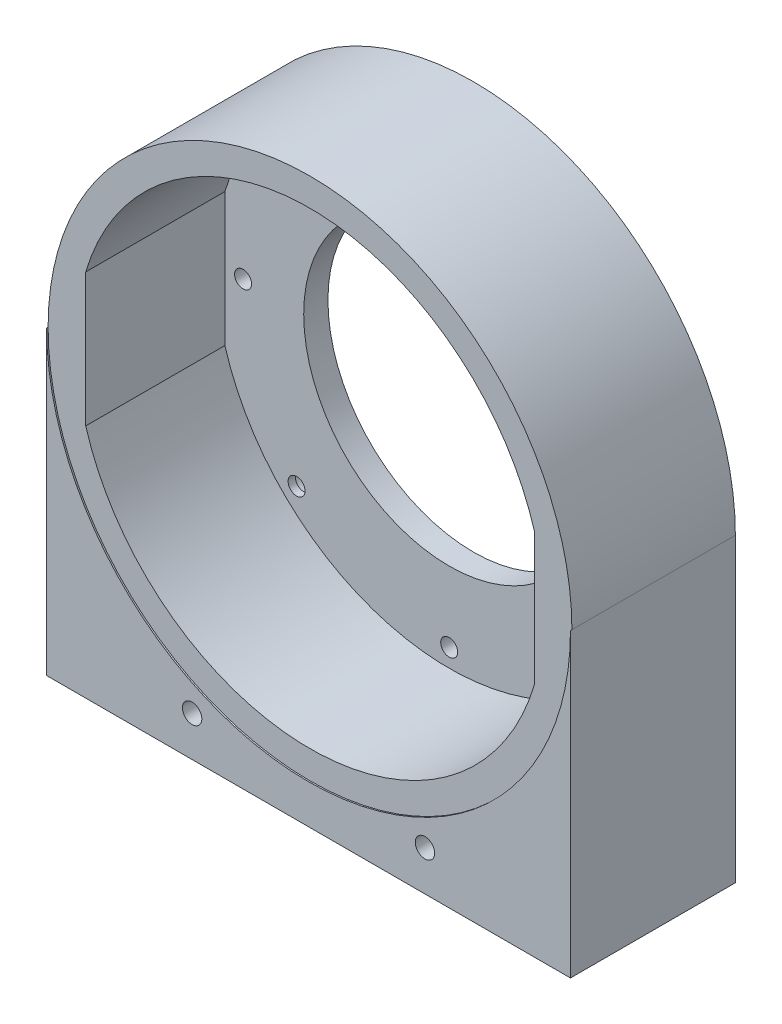
SolidWorks part; units mm, degrees
ref_plane "Front Plane" through (0, 0, 0) normal (0, 0, 1) x (1, 0, 0)
ref_plane "Top Plane" through (0, 0, 0) normal (0, 1, 0) x (1, 0, 0)
ref_plane "Right Plane" through (0, 0, 0) normal (1, 0, 0) x (0, 0, -1)
sketch "Sketch1" plane through (0, 0, 0) normal (0, 0, 1) x (1, 0, 0)
  circle A0 centre (0, 0) radius 48.25
extrude "Boss-Extrude1" add sketch "Sketch1" against normal blind 5 contours A0
sketch "Sketch2" plane through (0, 0, 0) normal (0, 0, 1) x (1, 0, 0)
  line L1 (-63.412, 28.4111) -> (-46.25, 28.4111)
  line L2 (-63.412, 28.4111) -> (-63.412, -28.4111)
  line L3 (-63.412, -28.4111) -> (-46.25, -28.4111)
  line L4 (-46.25, 28.4111) -> (-46.25, -28.4111)
  line L5 (46.25, 28.4111) -> (62.4025, 28.4111)
  line L6 (46.25, 28.4111) -> (46.25, -36.7758)
  line L7 (46.25, -36.7758) -> (62.4025, -36.7758)
  line L8 (62.4025, 28.4111) -> (62.4025, -36.7758)
  dimension "D1" = 92.5
  dimension "D2" = 46.25
extrude "Cut-Extrude1" cut sketch "Sketch2" against normal blind 8 contours L5 L8 L7 L6 | L1 L4 L3 L2
sketch "Sketch3" plane through (0, 0, 0) normal (0, 0, 1) x (1, 0, 0)
  circle A0 centre (0, 0) radius 30
extrude "Cut-Extrude2" cut sketch "Sketch3" against normal blind 8 contours A0
sketch "Sketch4" plane through (0, 0, 0) normal (0, 0, 1) x (1, 0, 0)
  circle A0 centre (-42.5, 0) radius 1.75
  circle A1 centre (42.5, 0) radius 1.75
  dimension "D1" = 85
  dimension "D2" = 42.5
sketch "Sketch6" plane through (0, 0, 0) normal (0, 0, 1) x (1, 0, 0)
  circle A0 centre (0, 44.5) radius 1.75
  dimension "D1" = 44.5
extrude "Cut-Extrude3" cut sketch "Sketch4" against normal blind 10 contours A1 | A0
extrude "Cut-Extrude4" cut sketch "Sketch6" against normal blind 10 contours A0
pattern_circular "CirPattern2" count 2 every 45 about axis through (0, 0, -8) along (0, 0, 1) of "Cut-Extrude4"
pattern_circular "CirPattern3" count 2 every 45 about axis through (0, 0, -8) along (0, 0, 1) of "Cut-Extrude4"
sketch "Sketch7" plane through (0, 0, 0) normal (0, 0, 1) x (1, 0, 0)
  circle A0 centre (0, -44.5) radius 1.75
  dimension "D1" = 44.5
extrude "Cut-Extrude5" cut sketch "Sketch7" against normal blind 10 contours A0
pattern_circular "CirPattern4" count 2 every 45 about axis through (0, 0, -8) along (0, 0, 1) of "Cut-Extrude5"
pattern_circular "CirPattern5" count 2 every 315 about axis through (0, 0, -8) along (0, 0, 1) of "Cut-Extrude5"
sketch "Sketch8" plane through (0, 0, -5) normal (0, 0, -1) x (-1, 0, 0)
  line L0 (-46.25, 13.7477) -> (-46.25, -13.7477)
  line L1 (46.25, 13.7477) -> (46.25, -13.7477)
  circle A0 centre (0, 0) radius 54
  arc A1 (-46.25, 13.7477) -> (46.25, 13.7477) centre (0, 0) cw
  arc A2 (-46.25, -13.7477) -> (46.25, -13.7477) centre (0, 0) ccw
extrude "Boss-Extrude3" add sketch "Sketch8" against normal blind 33.7 separate body
sketch "Sketch10" plane through (0, 0, -5) normal (0, 0, -1) x (-1, 0, 0)
  circle A0 centre (-31.4663, 31.4663) radius 3
sketch "Sketch11" plane through (0, 0, -5) normal (0, 0, -1) x (-1, 0, 0)
  circle A0 centre (31.4663, -31.4663) radius 3
sketch "Sketch12" plane through (0, 0, -5) normal (0, 0, -1) x (-1, 0, 0)
  circle A0 centre (-42.5, 0) radius 3
extrude "Cut-Extrude6" cut sketch "Sketch10" against normal blind 3.5 contours A0
extrude "Cut-Extrude7" cut sketch "Sketch12" against normal blind 3.5
extrude "Cut-Extrude8" cut sketch "Sketch11" against normal blind 3.5
sketch "Sketch13" plane through (0, 0, -5) normal (0, 0, -1) x (-1, 0, 0)
  line L0 (-54, 0) -> (-54, -62.0455)
  line L1 (-54, -62.0455) -> (54, -62.0455)
  line L2 (54, -62.0455) -> (54, 0)
  circle A0 centre (0, 0) radius 54 construction
  arc A1 (-54, 0) -> (54, 0) centre (0, 0) ccw
  point P7 (0, 0)
  point P10 (0, 0)
extrude "Boss-Extrude4" add sketch "Sketch13" against normal blind 34
sketch "Sketch14" plane through (0, 0, -5) normal (0, 0, -1) x (-1, 0, 0)
  circle A0 centre (-24, -53.7838) radius 2
  circle A1 centre (24, -53.7838) radius 2
  circle A2 centre (0, -44.5) radius 1.75 construction
  dimension "D1" = 48
  dimension "D2" = 24
extrude "Cut-Extrude9" cut sketch "Sketch14" against normal blind 34
